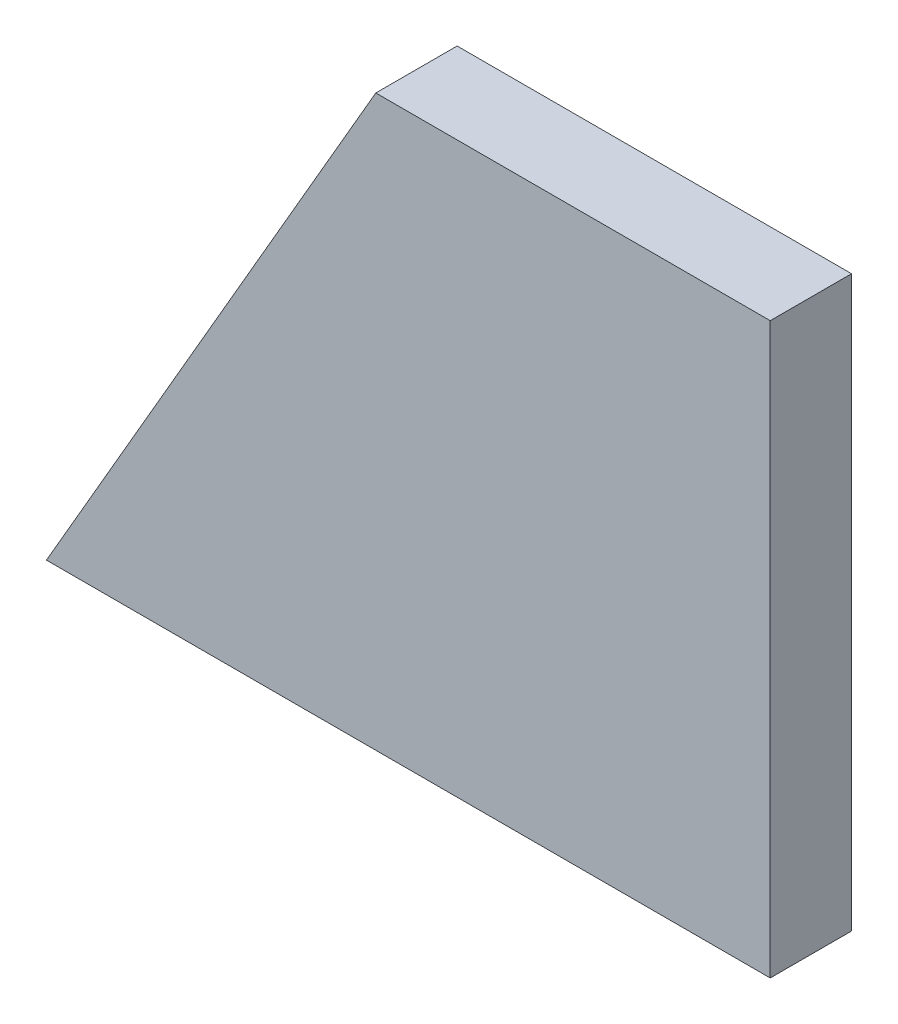
SolidWorks part; units mm, degrees
ref_plane "Спереди" through (0, 0, 0) normal (0, 0, 1) x (1, 0, 0)
ref_plane "Сверху" through (0, 0, 0) normal (0, 1, 0) x (1, 0, 0)
ref_plane "Справа" through (0, 0, 0) normal (1, 0, 0) x (0, 0, -1)
other "Configuration Table"
sketch "Эскиз1" plane through (0, 0, 0) normal (0, 0, 1) x (1, 0, 0)
  line L0 (-48.5, 70) -> (-89, 0)
  line L1 (0, 0) -> (-89, 0)
  line L2 (0, 0) -> (0, 70)
  line L3 (0, 70) -> (-48.5, 70)
  dimension "D1" = 70
  dimension "D2" = 80.8718
  dimension "D3" = 48.5
extrude "Бобышка-Вытянуть1" add sketch "Эскиз1" along normal blind 10
